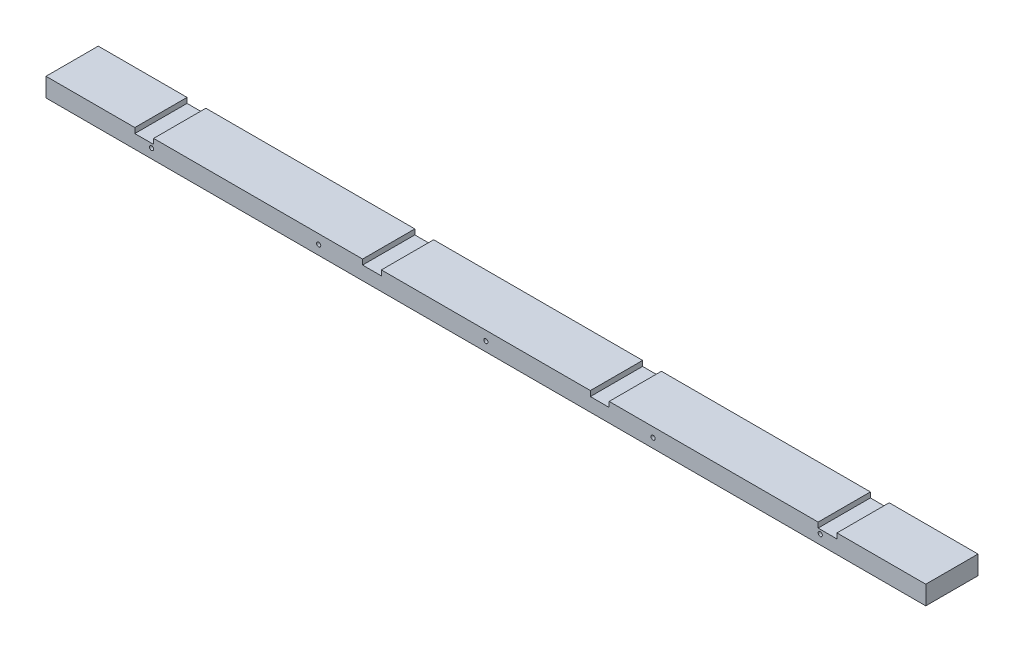
SolidWorks part; units mm, degrees
ref_plane "Front Plane" through (0, 0, 0) normal (0, 0, 1) x (1, 0, 0)
ref_plane "Top Plane" through (0, 0, 0) normal (0, 1, 0) x (1, 0, 0)
ref_plane "Right Plane" through (0, 0, 0) normal (1, 0, 0) x (0, 0, -1)
sketch "Sketch1" plane through (0, 0, 0) normal (0, 1, 0) x (1, 0, 0)
  line L1 (-421, -25) -> (421, -25)
  line L2 (-421, -25) -> (-421, 25)
  line L3 (-421, 25) -> (421, 25)
  line L4 (421, -25) -> (421, 25)
  line L5 (-421, -25) -> (421, 25) construction
  line L6 (-421, 25) -> (421, -25) construction
  point P0 (0, 0)
  dimension "D1" = 842
  dimension "D2" = 50
extrude "Boss-Extrude1" add sketch "Sketch1" along normal blind 18
sketch "Sketch2" plane through (0, 18, 0) normal (0, 1, 0) x (1, 0, 0)
  line L1 (-421, 25) -> (-421, -25) construction
  line L5 (-336, 129.5401) -> (-318, 129.5401)
  line L6 (-336, 129.5401) -> (-336, -104.7748)
  line L7 (-336, -104.7748) -> (-318, -104.7748)
  line L8 (-318, 129.5401) -> (-318, -104.7748)
  line L9 (-118, 129.5401) -> (-100, 129.5401)
  line L10 (-118, 129.5401) -> (-118, -104.7748)
  line L11 (-118, -104.7748) -> (-100, -104.7748)
  line L12 (-100, 129.5401) -> (-100, -104.7748)
  line L13 (100, 129.5401) -> (118, 129.5401)
  line L14 (100, 129.5401) -> (100, -104.7748)
  line L15 (100, -104.7748) -> (118, -104.7748)
  line L16 (118, 129.5401) -> (118, -104.7748)
  line L17 (318, 129.5401) -> (336, 129.5401)
  line L18 (318, 129.5401) -> (318, -104.7748)
  line L19 (318, -104.7748) -> (336, -104.7748)
  line L20 (336, 129.5401) -> (336, -104.7748)
  dimension "D2" = 85
  dimension "D3" = 18
  dimension "D4" = 18
  dimension "D6" = 200
  dimension "D7" = 18
  dimension "D8" = 200
  dimension "D9" = 200
  dimension "D10" = 18
extrude "Cut-Extrude1" cut sketch "Sketch2" against normal blind 5
hole_wizard "Ø4.0 (4) Diameter Hole1" positions "Sketch4" profile "Sketch3" hole size "Ø4.0" standard "ISO"
sketch "Sketch4" plane through (0, 0, 25) normal (0, 0, 1) x (1, 0, 0)
  point P0 (-320, 9)
  point P3 (-160, 9)
  point P6 (0, 9)
  point P9 (160, 9)
  point P12 (320, 9)
sketch "Sketch3" plane through (-320, 9, 25) normal (1, 0, 0) x (0, -1, 0)
  line L0 (0, 0) -> (0, 31.2017)
  line L1 (0, 31.2017) -> (2, 30)
  line L2 (2, 30) -> (2, 0)
  line L5 (2, 0) -> (0, 0)
  line L10 (0, 31.2017) -> (-2, 30) construction
  line L11 (0, -6.35) -> (0, 107.95) construction
  dimension "Hole Dia." = 4
  dimension "Hole Depth" = 30
  dimension "Drill Angle" = 118
hole_wizard "Ø4.0 (4) Diameter Hole2" positions "Sketch6" profile "Sketch5" hole size "Ø4.0" standard "ISO"
sketch "Sketch6" plane through (0, 0, -25) normal (0, 0, -1) x (-1, 0, 0)
  point P0 (-362.5, 9)
  point P2 (-217.5, 9)
  point P4 (-72.5, 9)
  point P6 (72.5, 9)
  point P8 (217.5, 9)
  point P10 (362.5, 9)
sketch "Sketch5" plane through (362.5, 9, -25) normal (1, 0, 0) x (0, 1, 0)
  line L0 (0, 0) -> (0, 31.2017)
  line L1 (0, 31.2017) -> (2, 30)
  line L2 (2, 30) -> (2, 0)
  line L5 (2, 0) -> (0, 0)
  line L10 (0, 31.2017) -> (-2, 30) construction
  line L11 (0, -6.35) -> (0, 107.95) construction
  dimension "Hole Dia." = 4
  dimension "Hole Depth" = 30
  dimension "Drill Angle" = 118
